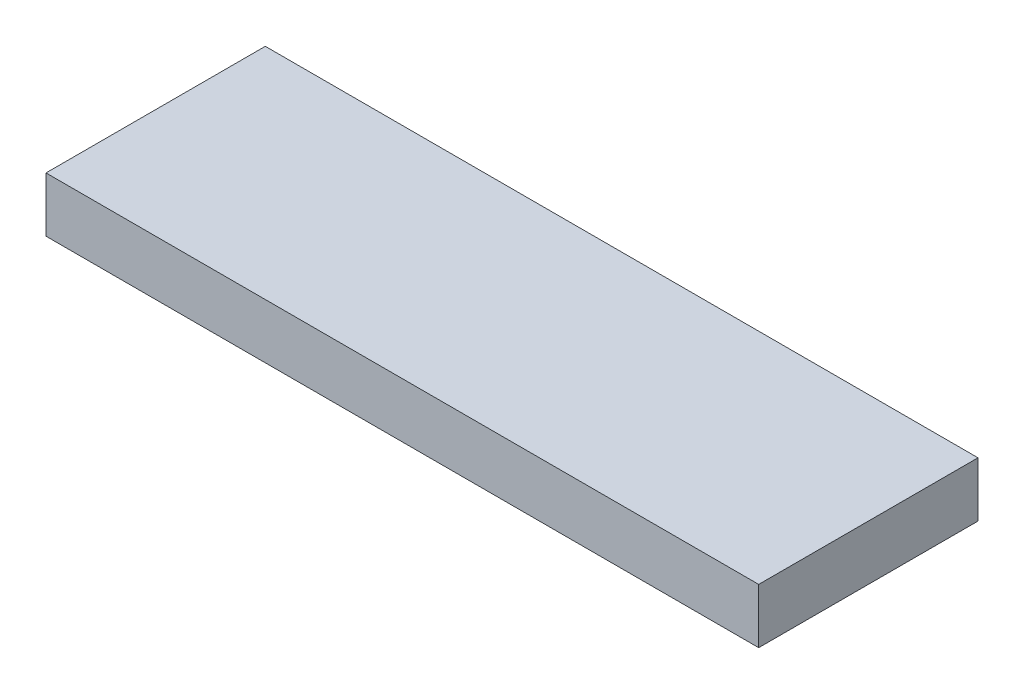
SolidWorks part; units mm, degrees
material "Miedź"
ref_plane "Front Plane" through (0, 0, 0) normal (0, 0, 1) x (1, 0, 0)
ref_plane "Top Plane" through (0, 0, 0) normal (0, 1, 0) x (1, 0, 0)
ref_plane "Right Plane" through (0, 0, 0) normal (1, 0, 0) x (0, 0, -1)
sketch "Szkic1" plane through (0, 0, 0) normal (0, 1, 0) x (1, 0, 0)
  line L1 (-6.5, -2) -> (6.5, -2)
  line L2 (-6.5, -2) -> (-6.5, 2)
  line L3 (-6.5, 2) -> (6.5, 2)
  line L4 (6.5, -2) -> (6.5, 2)
  line L5 (-6.5, -2) -> (6.5, 2) construction
  line L6 (-6.5, 2) -> (6.5, -2) construction
  point P0 (0, 0)
extrude "Dodanie-wyciągnięcie2" add sketch "Szkic1" along normal blind 1 contours L3 L4 L1 L2
